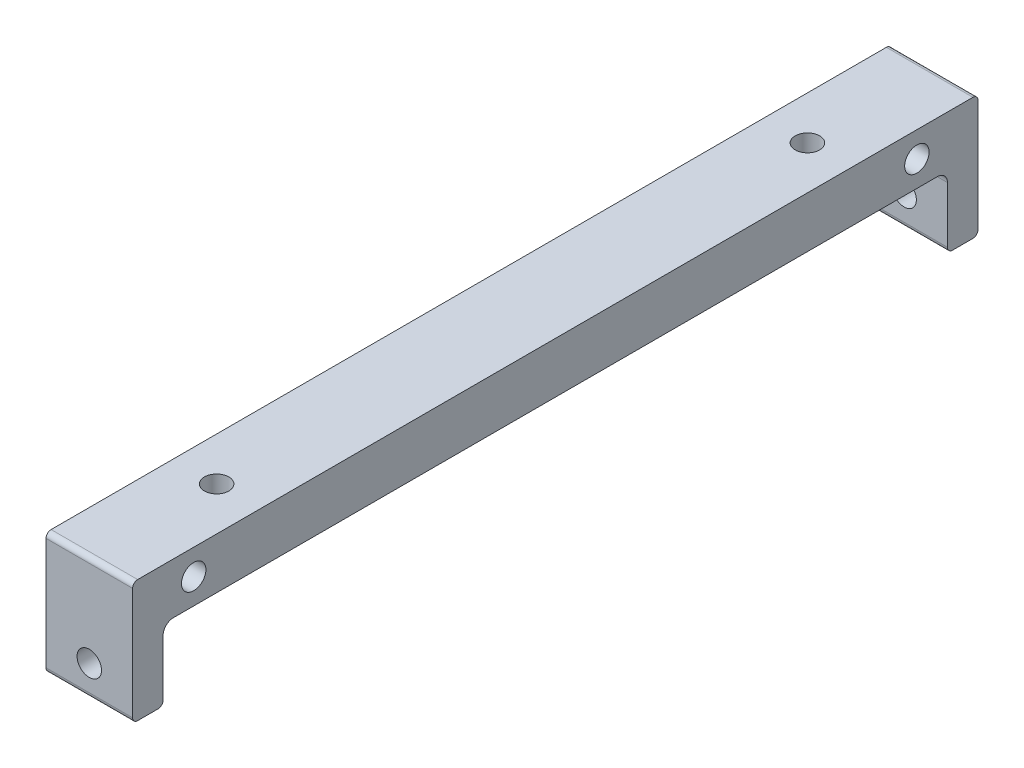
SolidWorks part; units mm, degrees
material "5052-H34"
ref_plane "Frontal" through (0, 0, 0) normal (0, 0, 1) x (1, 0, 0)
ref_plane "Superior" through (0, 0, 0) normal (0, 1, 0) x (1, 0, 0)
ref_plane "Direito" through (0, 0, 0) normal (1, 0, 0) x (0, 0, -1)
sketch "Sketch1" plane through (0, 0, 0) normal (0, 0, 1) x (1, 0, 0)
  line L1 (-4.25, -6) -> (4.25, -6)
  line L2 (-4.25, -6) -> (-4.25, 6)
  line L3 (-4.25, 6) -> (4.25, 6)
  line L4 (4.25, -6) -> (4.25, 6)
  line L5 (-4.25, -6) -> (4.25, 6) construction
  line L6 (-4.25, 6) -> (4.25, -6) construction
  point P0 (0, 0)
  dimension "D1" = 8.5
  dimension "D2" = 12
extrude "Boss-Extrude1" add sketch "Sketch1" along normal mid plane 83
sketch "Sketch2" plane through (4.25, 0, 0) normal (1, 0, 0) x (0, 0, -1)
  line L0 (-37.5, 1) -> (37.5, 1)
  line L1 (38.5, 0) -> (38.5, -6)
  line L2 (-41.5, -6) -> (41.5, -6) construction
  line L3 (38.5, -6) -> (-38.5, -6)
  line L4 (-38.5, -6) -> (-38.5, 0)
  line L5 (-41.5, 6) -> (41.5, 6) construction
  line L6 (-41.5, -6) -> (-41.5, 6) construction
  line L7 (41.5, -6) -> (41.5, 6) construction
  arc A0 (-37.5, 1) -> (-38.5, 0) centre (-37.5, 0) ccw
  arc A1 (37.5, 1) -> (38.5, 0) centre (37.5, 0) cw
  dimension "D4" = 1
  dimension "D5" = 1
  dimension "D1" = 5
  dimension "D2" = 3
  dimension "D3" = 3
extrude "Cut-Extrude1" cut sketch "Sketch2" against normal through all
fillet "Fillet1" radius 0.5 6 edges at (0, 6, -41.5) (0, 6, 41.5) (0, -6, -41.5) (0, -6, -38.5) (0, -6, 38.5) (0, -6, 41.5)
hole_wizard "M2 Hole1-J" positions "Sketch10" profile "Sketch9" hole size "M2" standard "DIN"
sketch "Sketch10" plane through (4.25, 0, 0) normal (1, 0, 0) x (0, 0, -1)
  line L0 (-41, 6) -> (41, 6) construction
  line L1 (-41.5, -5.5) -> (-41.5, 5.5) construction
  line L2 (41.5, -5.5) -> (41.5, 5.5) construction
  point P0 (-35.5, 3.5)
  point P2 (35.5, 3.5)
  dimension "D1" = 2.5
  dimension "D2" = 6
  dimension "D3" = 6
sketch "Sketch9" plane through (4.25, 3.5, 35.5) normal (0, 1, 0) x (0, 0, -1)
  line L0 (0, 0) -> (0, 5.721)
  line L1 (0, 5.721) -> (1.2, 5)
  line L2 (1.2, 5) -> (1.2, 0)
  line L5 (1.2, 0) -> (0, 0)
  line L10 (0, 5.721) -> (-1.2, 5) construction
  line L11 (0, -6.35) -> (0, 107.95) construction
  dimension "Hole Dia." = 2.4
  dimension "Hole Depth" = 5
  dimension "Drill Angle" = 118
hole_wizard "M2 Hole2-K" positions "Sketch19" profile "Sketch18" hole size "M2" standard "DIN"
sketch "Sketch19" plane through (-4.25, 0, 0) normal (-1, 0, 0) x (0, 0, 1)
  line L0 (-41.5, 5.5) -> (-41.5, -5.5) construction
  line L1 (41.5, 5.5) -> (41.5, -5.5) construction
  line L2 (41, 6) -> (-41, 6) construction
  point P0 (-21.5, 3.5)
  point P2 (21.5, 3.5)
  dimension "D1" = 20
  dimension "D2" = 20
  dimension "D3" = 2.5
sketch "Sketch18" plane through (-4.25, 3.5, -21.5) normal (0, 1, 0) x (0, 0, 1)
  line L0 (0, 0) -> (0, 5.721)
  line L1 (0, 5.721) -> (1.2, 5)
  line L2 (1.2, 5) -> (1.2, 0)
  line L5 (1.2, 0) -> (0, 0)
  line L10 (0, 5.721) -> (-1.2, 5) construction
  line L11 (0, -6.35) -> (0, 107.95) construction
  dimension "Hole Dia." = 2.4
  dimension "Hole Depth" = 5
  dimension "Drill Angle" = 118
hole_wizard "M2 Hole3-L" positions "Sketch8" profile "Sketch7" hole size "M2" standard "DIN"
sketch "Sketch8" plane through (0, 0, 41.5) normal (0, 0, 1) x (1, 0, 0)
  line L0 (4.25, -6) -> (-4.25, -6) construction
  point P0 (0, -3)
  dimension "D1" = 3
sketch "Sketch7" plane through (0, -3, 41.5) normal (1, 0, 0) x (0, -1, 0)
  line L0 (0, 0) -> (0, 10.721)
  line L1 (0, 10.721) -> (1.2, 10)
  line L2 (1.2, 10) -> (1.2, 0)
  line L5 (1.2, 0) -> (0, 0)
  line L10 (0, 10.721) -> (-1.2, 10) construction
  line L11 (0, -6.35) -> (0, 107.95) construction
  dimension "Hole Dia." = 2.4
  dimension "Hole Depth" = 10
  dimension "Drill Angle" = 118
hole_wizard "M2 Hole4-M" positions "Sketch15" profile "Sketch14" hole size "M2" standard "DIN" end condition through all
sketch "Sketch15" plane through (0, 6, 0) normal (0, 1, 0) x (1, 0, 0)
  line L0 (-4.25, -41) -> (-4.25, 41) construction
  line L1 (-4.25, 41.5) -> (4.25, 41.5) construction
  line L2 (4.25, -41.5) -> (-4.25, -41.5) construction
  point P0 (0, 29)
  point P2 (0, -29)
  dimension "D1" = 4.25
  dimension "D2" = 12.5
  dimension "D3" = 12.5
sketch "Sketch14" plane through (0, 6, -29) normal (1, 0, 0) x (0, 0, 1)
  line L0 (0, 0) -> (0, 12)
  line L1 (0, 12) -> (1.2, 12)
  line L2 (1.2, 12) -> (1.2, 0)
  line L5 (1.2, 0) -> (0, 0)
  line L11 (0, -6.35) -> (0, 107.95) construction
  dimension "Thru Hole Dia." = 2.4
  dimension "Thru Hole Depth" = 12
hole_wizard "M2 Hole5-N" positions "Sketch12" profile "Sketch11" hole size "M2" standard "DIN"
sketch "Sketch12" plane through (-4.25, 0, 0) normal (-1, 0, 0) x (0, 0, 1)
  line L0 (41, 6) -> (-41, 6) construction
  point P0 (0, 3.5)
  dimension "D1" = 2.5
sketch "Sketch11" plane through (-4.25, 3.5, 0) normal (0, 1, 0) x (0, 0, 1)
  line L0 (0, 0) -> (0, 4.721)
  line L1 (0, 4.721) -> (1.2, 4)
  line L2 (1.2, 4) -> (1.2, 0)
  line L5 (1.2, 0) -> (0, 0)
  line L10 (0, 4.721) -> (-1.2, 4) construction
  line L11 (0, -6.35) -> (0, 107.95) construction
  dimension "Hole Dia." = 2.4
  dimension "Hole Depth" = 4
  dimension "Drill Angle" = 118
hole_wizard "M2 Hole6-P" positions "Sketch17" profile "Sketch16" hole size "M2" standard "DIN"
sketch "Sketch17" plane through (0, 0, -41.5) normal (0, 0, -1) x (-1, 0, 0)
  line L0 (4.25, 5.5) -> (4.25, -5.5) construction
  line L1 (-4.25, 6) -> (4.25, 6) construction
  point P0 (0, -3)
  dimension "D1" = 4.25
  dimension "D2" = 9
sketch "Sketch16" plane through (0, -3, -41.5) normal (1, 0, 0) x (0, 1, 0)
  line L0 (0, 0) -> (0, 10.721)
  line L1 (0, 10.721) -> (1.2, 10)
  line L2 (1.2, 10) -> (1.2, 0)
  line L5 (1.2, 0) -> (0, 0)
  line L10 (0, 10.721) -> (-1.2, 10) construction
  line L11 (0, -6.35) -> (0, 107.95) construction
  dimension "Hole Dia." = 2.4
  dimension "Hole Depth" = 10
  dimension "Drill Angle" = 118
